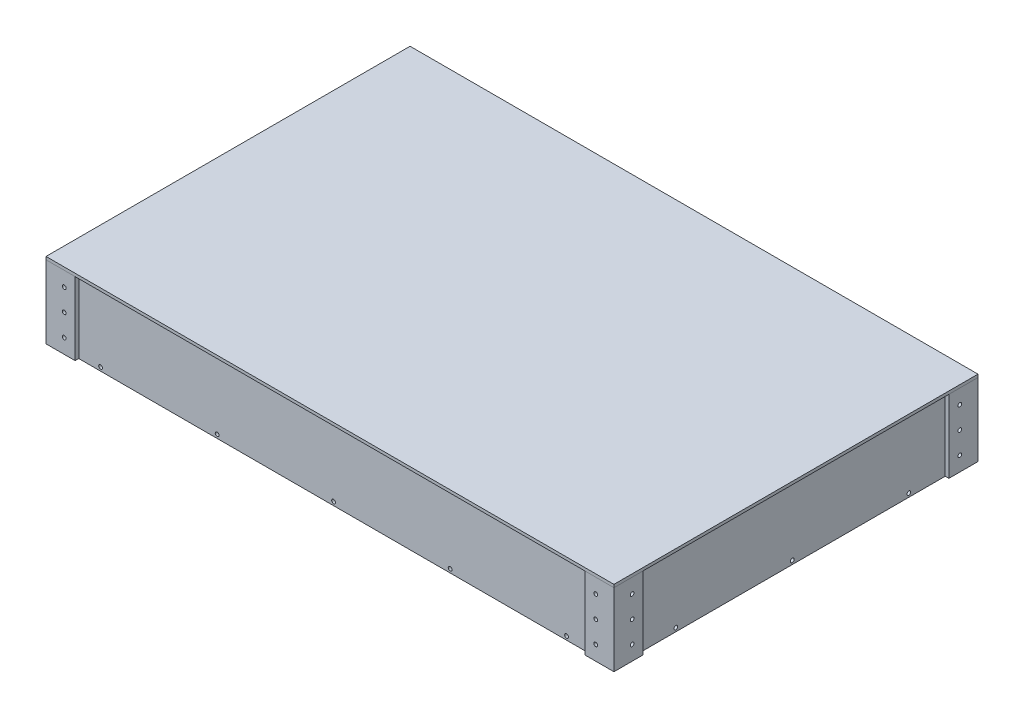
SolidWorks part; units mm, degrees
ref_plane "Front" through (0, 0, 0) normal (0, 0, 1) x (1, 0, 0)
ref_plane "Top" through (0, 0, 0) normal (0, 1, 0) x (1, 0, 0)
ref_plane "Right" through (0, 0, 0) normal (1, 0, 0) x (0, 0, -1)
sketch "Sketch1" plane through (0, 0, 0) normal (0, 1, 0) x (1, 0, 0)
  line L1 (-241.3, 152.4) -> (241.3, 152.4)
  line L2 (-241.3, 152.4) -> (-241.3, -152.4)
  line L3 (-241.3, -152.4) -> (241.3, -152.4)
  line L4 (241.3, 152.4) -> (241.3, -152.4)
  line L5 (-241.3, 152.4) -> (241.3, -152.4) construction
  line L6 (-241.3, -152.4) -> (241.3, 152.4) construction
  point P0 (0, 0)
  dimension "D1" = 482.6
  dimension "D2" = 304.8
extrude "Boss-Extrude1" add sketch "Sketch1" along normal blind 6.35
sketch "Sketch2" plane through (0, 6.35, 0) normal (0, 1, 0) x (1, 0, 0)
  line L0 (241.3, -152.4) -> (241.3, 152.4) construction
  line L1 (-241.3, 152.4) -> (241.3, 152.4)
  line L2 (-241.3, 152.4) -> (-241.3, 155.575)
  line L3 (-241.3, 155.575) -> (241.3, 155.575)
  line L4 (241.3, 152.4) -> (241.3, 155.575)
  line L5 (-241.3, 152.4) -> (241.3, 155.575) construction
  line L6 (-241.3, 155.575) -> (241.3, 152.4) construction
  line L7 (-241.3, -155.575) -> (241.3, -155.575)
  line L8 (-241.3, -155.575) -> (-241.3, -152.4)
  line L9 (-241.3, -152.4) -> (241.3, -152.4)
  line L10 (241.3, -155.575) -> (241.3, -152.4)
  line L11 (-241.3, -155.575) -> (241.3, -152.4) construction
  line L12 (-241.3, -152.4) -> (241.3, -155.575) construction
  line L13 (-241.3, 152.4) -> (-241.3, -152.4) construction
  line L14 (241.3, 152.4) -> (-241.3, 152.4) construction
  line L15 (-241.3, -152.4) -> (241.3, -152.4) construction
  point P0 (0, 153.9875)
  point P5 (0, -153.9875)
  dimension "D1" = 3.175
extrude "Boss-Extrude2" add sketch "Sketch2" along normal blind 57.15 and the other way up to surface (6.35 mm away) separate body other way up to face at (0, 0, 0)
sketch "Sketch3" plane through (0, 6.35, 0) normal (0, 1, 0) x (1, 0, 0)
  line L0 (241.3, -155.575) -> (-241.3, -155.575) construction
  line L1 (-241.3, 155.575) -> (-244.475, 155.575)
  line L2 (-241.3, 155.575) -> (-241.3, -155.575)
  line L3 (-241.3, -155.575) -> (-244.475, -155.575)
  line L4 (-244.475, 155.575) -> (-244.475, -155.575)
  line L6 (241.3, 155.575) -> (244.475, 155.575)
  line L7 (241.3, 155.575) -> (241.3, -155.575)
  line L8 (241.3, -155.575) -> (244.475, -155.575)
  line L9 (244.475, 155.575) -> (244.475, -155.575)
  dimension "D1" = 3.175
extrude "Boss-Extrude3" add sketch "Sketch3" along normal up to surface and the other way up to surface separate body
sketch "Sketch4" plane through (0, 0, 0) normal (0, -1, 0) x (1, 0, 0)
  line L0 (-244.475, -155.575) -> (-222.25, -155.575)
  line L2 (-222.25, -155.575) -> (-222.25, -158.75)
  line L3 (-222.25, -158.75) -> (-247.65, -158.75)
  line L4 (-247.65, -158.75) -> (-247.65, -133.35)
  line L5 (-247.65, -133.35) -> (-244.475, -133.35)
  line L7 (-244.475, -133.35) -> (-244.475, -155.575)
  line L8 (-244.475, 155.575) -> (-244.475, -155.575) construction
  line L9 (-241.3, -155.575) -> (241.3, -155.575) construction
  dimension "D1" = 3.175
  dimension "D2" = 25.4
  dimension "D3" = 25.4
extrude "Boss-Extrude4" add sketch "Sketch4" against normal up to surface (63.5 mm away) separate body up to face at (0, 63.5, -153.9875)
mirror "Mirror1" about plane through (0, 0, 0) normal (1, 0, 0) of bodies 184
mirror "Mirror2" about plane through (0, 0, 0) normal (0, 0, 1) of bodies 184 185
sketch "Sketch5" plane through (0, 0, -155.575) normal (0, 0, -1) x (-1, 0, 0)
  line L0 (-241.3, 31.75) -> (-222.25, 31.75) construction
  line L1 (-241.3, 0) -> (-241.3, 63.5) construction
  line L2 (-222.25, 63.5) -> (-222.25, 0) construction
  line L3 (-231.775, 50.8) -> (-231.775, 12.7) construction
  circle A0 centre (-231.775, 50.8) radius 1.651
  circle A1 centre (-231.775, 31.75) radius 1.651
  circle A2 centre (-231.775, 12.7) radius 1.651
  point P8 (-231.775, 31.75)
  dimension "D2" = 3.302
  dimension "D1" = 38.1
extrude "Cut-Extrude1" cut sketch "Sketch5" against normal through all
mirror "Mirror3" about plane through (0, 0, 0) normal (1, 0, 0) of "Cut-Extrude1"
sketch "Sketch6" plane through (-247.65, 0, 0) normal (-1, 0, 0) x (0, 0, 1)
  line L0 (-152.4, 31.75) -> (-133.35, 31.75) construction
  line L1 (-133.35, 63.5) -> (-133.35, 0) construction
  line L2 (-152.4, 0) -> (-152.4, 63.5) construction
  line L3 (-142.875, 50.8) -> (-142.875, 12.7) construction
  circle A0 centre (-142.875, 50.8) radius 1.651
  circle A1 centre (-142.875, 31.75) radius 1.651
  circle A2 centre (-142.875, 12.7) radius 1.651
  point P2 (-142.875, 31.75)
  point P5 (-142.875, 31.75)
  dimension "D2" = 3.302
  dimension "D1" = 38.1
extrude "Cut-Extrude2" cut sketch "Sketch6" against normal through all
mirror "Mirror4" about plane through (0, 0, 0) normal (0, 0, 1) of "Cut-Extrude2"
sketch "Sketch7" plane through (0, 0, 155.575) normal (0, 0, 1) x (1, 0, 0)
  line L0 (-247.65, 3.175) -> (247.65, 3.175) construction
  line L1 (-247.65, 6.35) -> (-247.65, 0) construction
  line L2 (241.3, 0) -> (-241.3, 0) construction
  line L3 (-241.3, 6.35) -> (241.3, 6.35) construction
  line L4 (247.65, 63.5) -> (247.65, 0) construction
  circle A0 centre (-203.2, 3.175) radius 1.651
  circle A1 centre (0, 3.175) radius 1.651
  circle A2 centre (203.2, 3.175) radius 1.651
  circle A3 centre (101.6, 3.175) radius 1.651
  circle A4 centre (-101.6, 3.175) radius 1.651
  dimension "D1" = 3.302
  dimension "D3" = 3.302
  dimension "D4" = 101.6
  dimension "D5" = 101.6
  dimension "D6" = 203.2
  dimension "D2" = 203.2
extrude "Cut-Extrude3" cut sketch "Sketch7" against normal through all and the other way through all
sketch "Sketch8" plane through (244.475, 0, 0) normal (1, 0, 0) x (0, 0, -1)
  line L0 (-158.75, 3.175) -> (158.75, 3.175) construction
  line L1 (-158.75, 63.5) -> (-158.75, 0) construction
  line L2 (158.75, 63.5) -> (158.75, 0) construction
  line L3 (0, 0) -> (0, 6.35) construction
  line L4 (-152.4, 6.35) -> (152.4, 6.35) construction
  circle A0 centre (0, 3.175) radius 1.651
  circle A1 centre (101.6, 3.175) radius 1.651
  circle A2 centre (-101.6, 3.175) radius 1.651
  point P12 (0, 3.175)
  dimension "D1" = 3.302
  dimension "D2" = 101.6
  dimension "D3" = 101.6
extrude "Cut-Extrude4" cut sketch "Sketch8" against normal through all
sketch "Sketch9" plane through (0, 63.5, 0) normal (0, 1, 0) x (1, 0, 0)
  line L1 (247.65, -158.75) -> (-247.65, -158.75)
  line L2 (247.65, -158.75) -> (247.65, 158.75)
  line L3 (247.65, 158.75) -> (-247.65, 158.75)
  line L4 (-247.65, -158.75) -> (-247.65, 158.75)
extrude "Boss-Extrude5" add sketch "Sketch9" along normal blind 2.54 separate body
